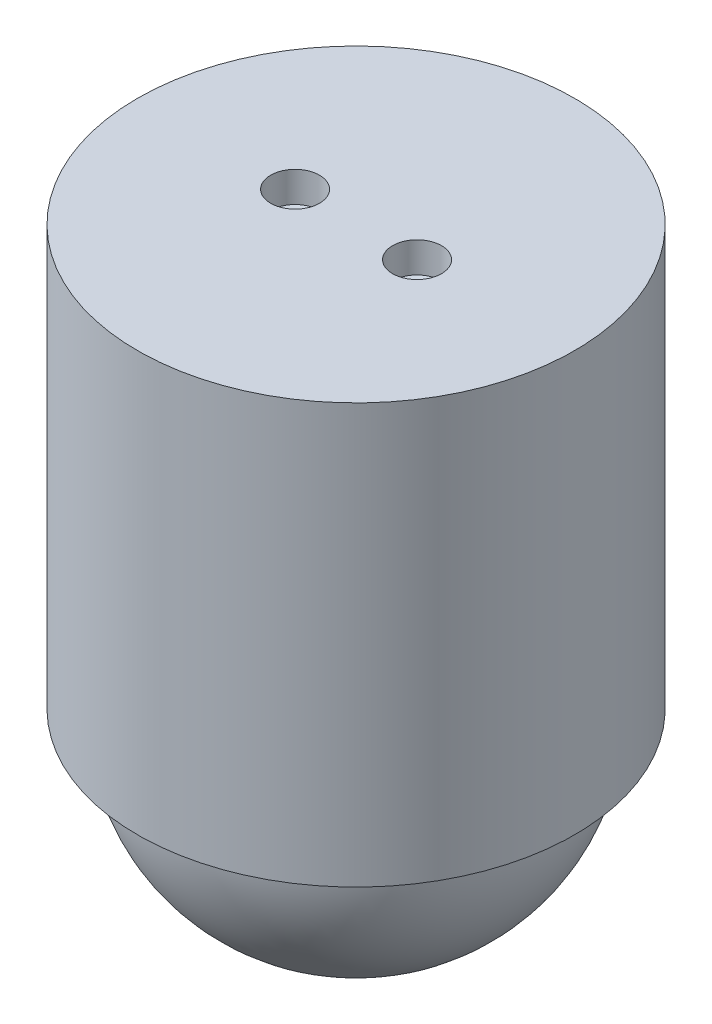
SolidWorks part; units mm, degrees
ref_plane "Front Plane" through (0, 0, 0) normal (0, 0, 1) x (1, 0, 0)
ref_plane "Top Plane" through (0, 0, 0) normal (0, 1, 0) x (1, 0, 0)
ref_plane "Right Plane" through (0, 0, 0) normal (1, 0, 0) x (0, 0, -1)
sketch "Sketch1" plane through (0, 0, 0) normal (0, 0, 1) x (1, 0, 0)
  line L0 (0, 0) -> (-10.922, 0)
  line L1 (-10.922, 0) -> (-10.922, -20.955)
  line L2 (-10.922, -20.955) -> (-9.525, -20.955)
  line L3 (0, 0) -> (0, -30.48)
  arc A0 (0, -30.48) -> (-9.525, -20.955) centre (0, -20.955) cw
  dimension "D1" = 9.525
  dimension "D2" = 9.525
  dimension "D3" = 10.922
  dimension "D4" = 30.48
revolve "Revolve1" add sketch "Sketch1" angle 360 about L3
hole_wizard "#2 Clearance Hole1" positions "Sketch4" profile "Sketch2" hole size "#2" standard "ANSI Inch"
sketch "Sketch4" plane through (0, 0, 0) normal (0, 1, 0) x (1, 0, 0)
  line L0 (-13.9547, 0) -> (12.9985, 0) construction
  line L1 (0, 11.9825) -> (0, -12.102) construction
  point P0 (3.048, 0)
  point P2 (-3.048, 0)
  dimension "D1" = 3.048
  dimension "D2" = 6.096
sketch "Sketch2" plane through (3.048, 0, 0) normal (1, 0, 0) x (0, 0, 1)
  line L0 (0, 0) -> (0, 2.2566)
  line L1 (0, 2.2566) -> (1.2192, 1.524)
  line L2 (1.2192, 1.524) -> (1.2192, 0)
  line L5 (1.2192, 0) -> (0, 0)
  line L10 (0, 2.2566) -> (-1.2192, 1.524) construction
  line L11 (0, -6.35) -> (0, 107.95) construction
  dimension "Hole Dia." = 2.4384
  dimension "Hole Depth" = 1.524
  dimension "Drill Angle" = 118
